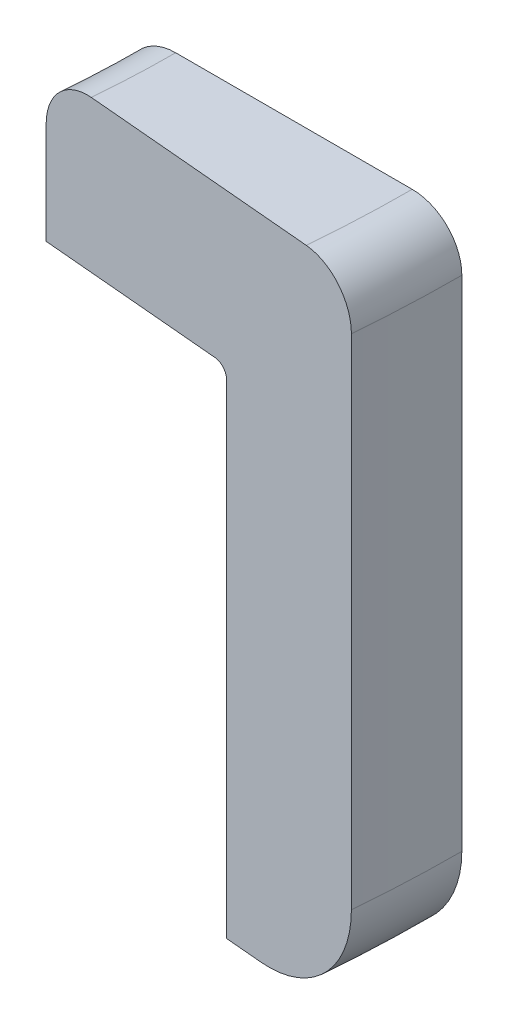
SolidWorks part; units mm, degrees
ref_plane "Ön Düzlem" through (0, 0, 0) normal (0, 0, 1) x (1, 0, 0)
ref_plane "Üst Düzlem" through (0, 0, 0) normal (0, 1, 0) x (1, 0, 0)
ref_plane "Sağ Düzlem" through (0, 0, 0) normal (1, 0, 0) x (0, 0, -1)
sketch "Sketch1" plane through (0, 0, 0) normal (0, 0, 1) x (1, 0, 0)
  line L0 (-43.4, 20.1096) -> (-43.4, -4.5349) construction
  line L2 (0, 0) -> (0, 13.5)
  line L4 (5.5331, 0) -> (5.5331, 14)
  line L5 (-0.5, 14) -> (-8, 14)
  line L6 (5.5331, 14) -> (5.5331, 18.1096)
  line L7 (3.5331, 20.1096) -> (-6, 20.1096)
  line L8 (-8, 14) -> (-8, 18.1096)
  line L10 (0, 0) -> (0, -6)
  line L11 (0, -6) -> (1.5331, -6)
  line L12 (5.5331, 0) -> (5.5331, -2)
  arc A0 (-6, 20.1096) -> (-8, 18.1096) centre (-6, 18.1096) ccw
  arc A1 (1.5331, -6) -> (5.5331, -2) centre (1.5331, -2) ccw
  arc A2 (5.5331, 18.1096) -> (3.5331, 20.1096) centre (3.5331, 18.1096) ccw
  arc A3 (0, 13.5) -> (-0.5, 14) centre (-0.5, 13.5) ccw
  dimension "D3" = 2
  dimension "D4" = 4
  dimension "D5" = 2
  dimension "D6" = 0.5
  dimension "D1" = 14
  dimension "D2" = 8
  dimension "D7" = 43.4
revolve "Revolve1" add sketch "Sketch1" angle 5 about L0
